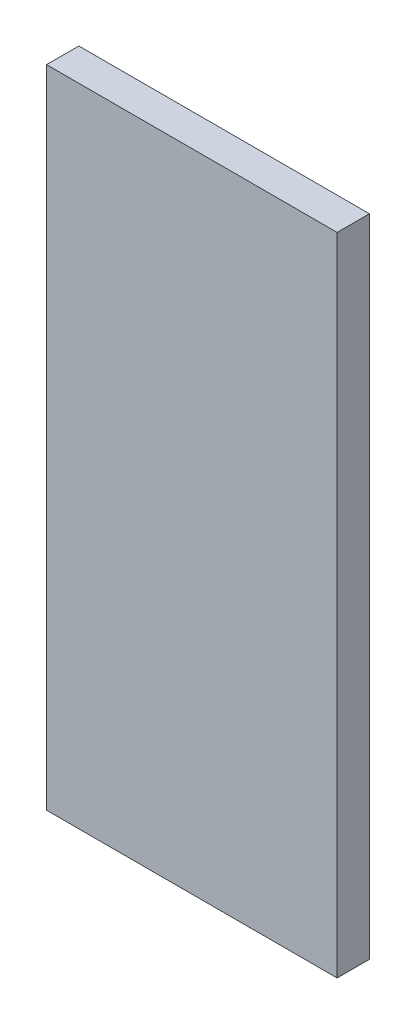
SolidWorks part; units mm, degrees
other "Папка сварных швов"
material "Ст 3 ГОСТ 380-88"
ref_plane "Front" through (0, 0, 0) normal (0, 0, 1) x (1, 0, 0)
ref_plane "Top" through (0, 0, 0) normal (0, 1, 0) x (1, 0, 0)
ref_plane "Right" through (0, 0, 0) normal (1, 0, 0) x (0, 0, -1)
sketch "Sketch1" plane through (0, 0, 0) normal (0, 0, 1) x (1, 0, 0)
  line L1 (-22.5, -50) -> (22.5, -50)
  line L2 (-22.5, -50) -> (-22.5, 50)
  line L3 (-22.5, 50) -> (22.5, 50)
  line L4 (22.5, -50) -> (22.5, 50)
  line L5 (-22.5, -50) -> (22.5, 50) construction
  line L6 (-22.5, 50) -> (22.5, -50) construction
  point P0 (0, 0)
  dimension "D1" = 45
  dimension "D2" = 100
extrude "Boss-Extrude1" add sketch "Sketch1" along normal blind 5
